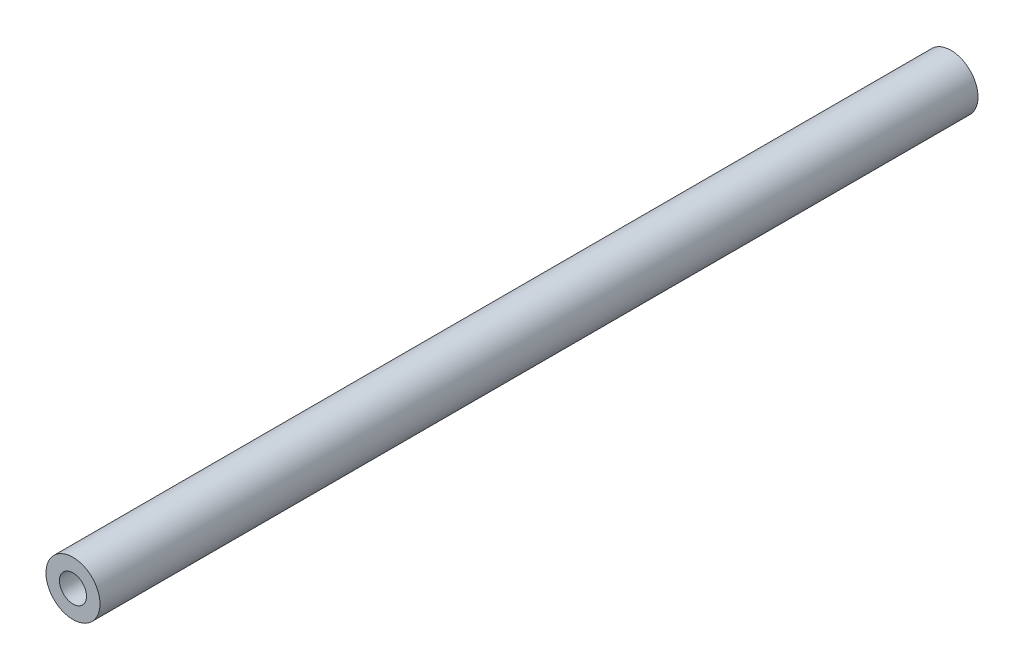
SolidWorks part; units mm, degrees
ref_plane "前视基准面" through (0, 0, 0) normal (0, 0, 1) x (1, 0, 0)
ref_plane "上视基准面" through (0, 0, 0) normal (0, 1, 0) x (1, 0, 0)
ref_plane "右视基准面" through (0, 0, 0) normal (1, 0, 0) x (0, 0, -1)
sketch "草图1" plane through (0, 0, 0) normal (0, 0, 1) x (1, 0, 0)
  circle A0 centre (0, 0) radius 8
  dimension "D1" = 16
extrude "凸台-拉伸1" add sketch "草图1" along normal blind 260
sketch "草图2" plane through (0, 0, 260) normal (0, 0, 1) x (1, 0, 0)
  circle A0 centre (0, 0) radius 4
extrude "切除-拉伸1" cut sketch "草图2" against normal blind 20
sketch "草图3" plane through (0, 0, 0) normal (0, 0, -1) x (-1, 0, 0)
  circle A0 centre (0, 0) radius 4
  dimension "D1" = 8
extrude "切除-拉伸2" cut sketch "草图3" against normal blind 20
